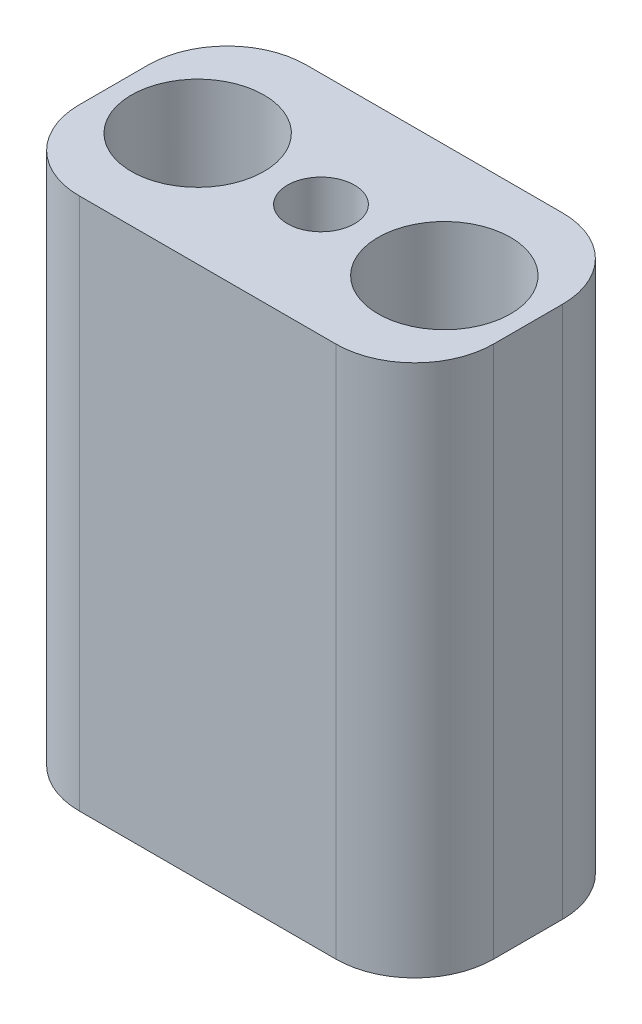
SolidWorks part; units mm, degrees
material "PLA_grey"
ref_plane "Front Plane" through (0, 0, 0) normal (0, 0, 1) x (1, 0, 0)
ref_plane "Top Plane" through (0, 0, 0) normal (0, 1, 0) x (1, 0, 0)
ref_plane "Right Plane" through (0, 0, 0) normal (1, 0, 0) x (0, 0, -1)
sketch "Sketch1" plane through (0, 0, 0) normal (0, 0, 1) x (1, 0, 0)
  line L0 (27.5, 9) -> (47.5, 9) construction
  line L1 (-47.5, 0) -> (47.5, 0) construction
  line L2 (-47.5, 0) -> (-47.5, 9) construction
  line L3 (-47.5, 9) -> (-27.5, 9) construction
  line L4 (47.5, 0) -> (47.5, 9) construction
  line L5 (-27.5, 54) -> (27.5, 54) construction
  line L6 (-27.5, 54) -> (-27.5, 9) construction
  line L8 (27.5, 54) -> (27.5, 9) construction
  line L10 (-21, 0) -> (21, 0)
  line L11 (-21, 0) -> (-21, 54)
  line L12 (-21, 54) -> (21, 54)
  line L13 (21, 0) -> (21, 54)
  point P8 (0, 54)
  dimension "D1" = 95
  dimension "D2" = 9
  dimension "D3" = 55
  dimension "D4" = 54
  dimension "D5" = 42
extrude "Boss-Extrude1" add sketch "Sketch1" along normal blind 23
hole_wizard "M8 Tapped Hole1" positions "Sketch6" profile "Sketch7" tap size "M8" standard "ISO"
sketch "Sketch6" plane through (0, 54, 0) normal (0, 1, 0) x (1, 0, 0)
  line L1 (0, 0) -> (0, -23) construction
  line L2 (21, -23) -> (-21, -23) construction
  point P34 (0, -11.5)
cosmetic thread "Hole Thread1" parameters "D1"=13, "D2"=8
sketch "Sketch7" plane through (0, 54, 11.5) normal (1, 0, 0) x (0, 0, 1)
  line L0 (0, 0) -> (0, 17.0429)
  line L1 (0, 17.0429) -> (3.4, 15)
  line L2 (3.4, 15) -> (3.4, 0)
  line L5 (3.4, 0) -> (0, 0)
  line L10 (0, 17.0429) -> (-3.4, 15) construction
  line L11 (0, -6.35) -> (0, 107.95) construction
  dimension "Tap Drill Dia." = 6.8
  dimension "Tap Drill Depth" = 15
  dimension "Drill Angle" = 118
ref_plane "Plane1" through (0, 35, 0) normal (0, -1, 0) x (-1, 0, 0)
hole_wizard "CSK for M6 Hex Socket Countersunk Cap Screw2" positions "Sketch4" profile "Sketch5" countersink size "M6" standard "ISO"
sketch "Sketch4" plane through (0, 35, 0) normal (0, 1, 0) x (1, 0, 0)
  line L1 (12.5, -11.5) -> (-12.5, -11.5) construction
  line L5 (0, 0) -> (0, -23) construction
  line L6 (21, 0) -> (-21, 0) construction
  line L7 (21, -23) -> (-21, -23) construction
  point P0 (12.5, -11.5)
  point P2 (-12.5, -11.5)
  point P12 (0, -11.5)
  dimension "D1" = 25
sketch "Sketch5" plane through (12.5, 35, 11.5) normal (1, 0, 0) x (0, 0, 1)
  line L0 (0, 0) -> (0, 35)
  line L1 (0, 35) -> (3.3, 35)
  line L2 (3.3, 35) -> (3.3, 3.42)
  line L3 (3.3, 3.42) -> (6.72, 0)
  line L5 (6.72, 0) -> (0, 0)
  line L6 (-3.3, 3.42) -> (-6.72, 0) construction
  line L11 (0, -6.35) -> (0, 107.95) construction
  dimension "Thru Hole Dia." = 6.6
  dimension "Thru Hole Depth" = 35
  dimension "Near C'Sink Dia." = 13.44
  dimension "Near C'Sink Angle" = 90
fillet "Fillet1" radius 8 4 edges at (-21, 27, 23) (21, 27, 23) (-21, 27, 0) (21, 27, 0)
sketch "Sketch8" plane through (0, 35, 0) normal (0, -1, 0) x (-1, 0, 0)
  circle A0 centre (12.5, -11.5) radius 6.72
  circle A1 centre (12.5, -11.5) radius 6.72
  circle A2 centre (-12.5, -11.5) radius 6.72
  circle A3 centre (-12.5, -11.5) radius 6.72
extrude "Cut-Extrude1" cut sketch "Sketch8" against normal through all
